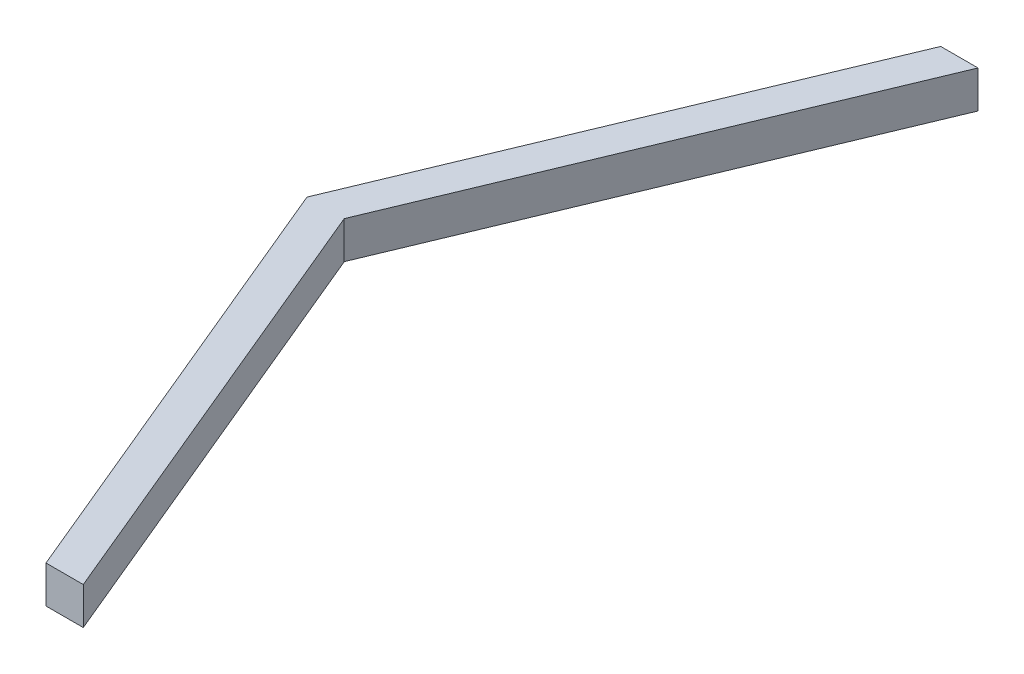
SolidWorks part; units mm, degrees
ref_plane "Front Plane" through (0, 0, 0) normal (0, 0, 1) x (1, 0, 0)
ref_plane "Top Plane" through (0, 0, 0) normal (0, 1, 0) x (1, 0, 0)
ref_plane "Right Plane" through (0, 0, 0) normal (1, 0, 0) x (0, 0, -1)
sketch "Sketch1" plane through (0, 0, 0) normal (0, 1, 0) x (1, 0, 0)
  line L0 (0, 304.8) -> (0, -304.8) construction
  line L1 (0, 304.8) -> (-25.4, 304.8)
  line L2 (-25.4, 304.8) -> (-152.4, 0)
  line L3 (-152.4, 0) -> (-25.4, -304.8)
  line L4 (-25.4, -304.8) -> (0, -304.8)
  line L5 (0, -304.8) -> (-127, 0)
  line L6 (-127, 0) -> (0, 304.8)
  line L7 (-193.3396, 0) -> (0, 0) construction
  point P7 (0, 0)
  dimension "D1" = 609.6
  dimension "D2" = 25.4
  dimension "D3" = 127
extrude "Boss-Extrude1" add sketch "Sketch1" along normal blind 25.4
